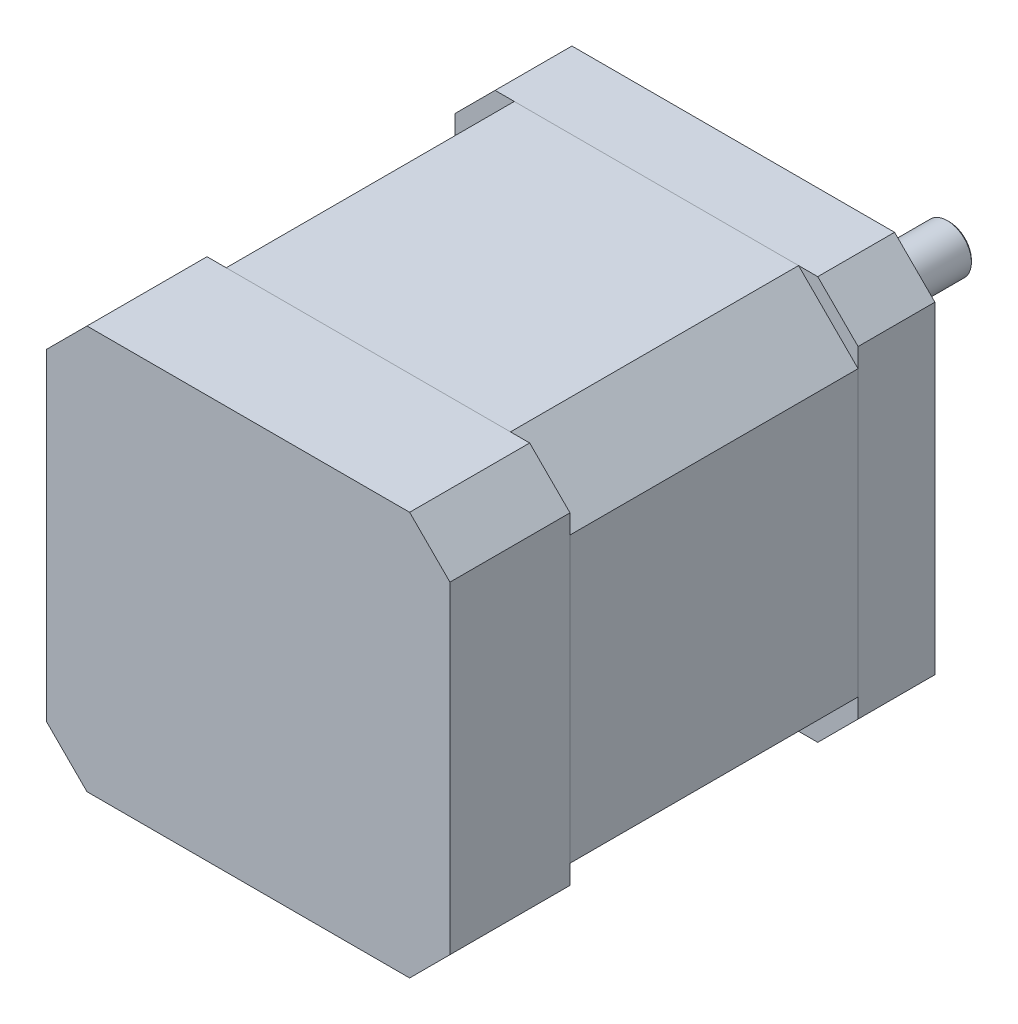
SolidWorks part; units mm, degrees
ref_plane "Plan de face" through (0, 0, 0) normal (0, 0, 1) x (1, 0, 0)
ref_plane "Plan de dessus" through (0, 0, 0) normal (0, 1, 0) x (1, 0, 0)
ref_plane "Plan de droite" through (0, 0, 0) normal (1, 0, 0) x (0, 0, -1)
sketch "Esquisse1" plane through (0, 0, 0) normal (0, 0, 1) x (1, 0, 0)
  line L1 (-21, 21) -> (21, 21)
  line L2 (-21, 21) -> (-21, -21)
  line L3 (-21, -21) -> (21, -21)
  line L4 (21, 21) -> (21, -21)
  line L5 (-21, 21) -> (21, -21) construction
  line L6 (-21, -21) -> (21, 21) construction
  point P0 (0, 0)
  dimension "D1" = 42
  dimension "D2" = 42
extrude "Boss.-Extru.1" add sketch "Esquisse1" along normal blind 8
chamfer "Chanfrein1" distance 4.2 angle 45 4 edges at (-21, -21, 4) (-21, 21, 4) (21, 21, 4) (21, -21, 4)
sketch "Esquisse3" plane through (0, 0, 8) normal (0, 0, 1) x (1, 0, 0)
  line L0 (-21, 14.8) -> (-14.8, 21)
  line L1 (-14.8, 21) -> (14.8, 21)
  line L2 (-21, 14.8) -> (-21, -14.8)
  line L3 (-14.8, -21) -> (14.8, -21)
  line L4 (21, 14.8) -> (21, -14.8)
  line L5 (-21, 21) -> (21, -21) construction
  line L6 (-21, -21) -> (21, 21) construction
  line L7 (14.8, 21) -> (21, 14.8)
  line L8 (14.8, -21) -> (21, -14.8)
  line L9 (-21, -14.8) -> (-14.8, -21)
  point P0 (0, 0)
  dimension "D1" = 42
  dimension "D2" = 42
extrude "Boss.-Extru.2" add sketch "Esquisse3" along normal blind 30 separate body
sketch "Esquisse4" plane through (0, 0, 38) normal (0, 0, 1) x (1, 0, 0)
  line L1 (-21, -21) -> (21, -21)
  line L2 (-21, -21) -> (-21, 21)
  line L3 (-21, 21) -> (21, 21)
  line L4 (21, -21) -> (21, 21)
  line L5 (-21, -21) -> (21, 21) construction
  line L6 (-21, 21) -> (21, -21) construction
  point P0 (0, 0)
  dimension "D1" = 42
  dimension "D2" = 42
extrude "Boss.-Extru.3" add sketch "Esquisse4" along normal blind 12.5 separate body
chamfer "Chanfrein3" distance 4.2 angle 45 4 edges at (21, 21, 44.25) (21, -21, 44.25) (-21, -21, 44.25) (-21, 21, 44.25)
sketch "Esquisse5" plane through (0, 0, 0) normal (0, 0, -1) x (-1, 0, 0)
  circle A0 centre (0, 0) radius 11
  dimension "D1" = 22
extrude "Boss.-Extru.4" add sketch "Esquisse5" along normal blind 2
sketch "Esquisse6" plane through (0, 0, -2) normal (0, 0, -1) x (-1, 0, 0)
  circle A0 centre (0, 0) radius 4.5
  dimension "D1" = 9
extrude "Enlèv. mat.-Extru.1" cut sketch "Esquisse6" against normal blind 3
sketch "Esquisse7" plane through (0, 0, 1) normal (0, 0, -1) x (-1, 0, 0)
  circle A0 centre (0, 0) radius 2.5
  dimension "D1" = 5
extrude "Boss.-Extru.5" add sketch "Esquisse7" along normal blind 23.5
chamfer "Chanfrein4" distance 0.2 angle 45 1 edges at (-2.5, 0, -22.5)
sketch "Esquisse8" plane through (0, 0, 0) normal (0, 0, -1) x (-1, 0, 0)
  line L1 (-15.5, 15.5) -> (15.5, 15.5) construction
  line L2 (-15.5, 15.5) -> (-15.5, -15.5) construction
  line L3 (-15.5, -15.5) -> (15.5, -15.5) construction
  line L4 (15.5, 15.5) -> (15.5, -15.5) construction
  line L5 (-15.5, 15.5) -> (15.5, -15.5) construction
  line L6 (-15.5, -15.5) -> (15.5, 15.5) construction
  circle A0 centre (-15.5, 15.5) radius 1.5
  circle A1 centre (15.5, 15.5) radius 1.5
  circle A2 centre (15.5, -15.5) radius 1.5
  circle A3 centre (-15.5, -15.5) radius 1.5
  point P0 (0, 0)
  dimension "D3" = 3
  dimension "D1" = 31
  dimension "D2" = 31
extrude "Enlèv. mat.-Extru.2" cut sketch "Esquisse8" against normal blind 5
chamfer "Chanfrein5" distance 0.2 angle 45 4 edges at (14, -15.5, 0) (-17, -15.5, 0) (-17, 15.5, 0) (14, 15.5, 0)
sketch "Esquisse9" plane through (-21, 0, 0) normal (-1, 0, 0) x (0, 0, 1)
  line L0 (41.5, 0) -> (38, 0) construction
  line L1 (38, -4) -> (45, -4)
  line L2 (38, -4) -> (38, 4)
  line L3 (38, 4) -> (45, 4)
  line L4 (45, -4) -> (45, 4)
  line L5 (38, -4) -> (45, 4) construction
  line L6 (38, 4) -> (45, -4) construction
  line L7 (38, 16.8) -> (38, -16.8) construction
  point P0 (41.5, 0)
  dimension "D1" = 7
  dimension "D2" = 8
extrude "Enlèv. mat.-Extru.3" cut sketch "Esquisse9" against normal blind 2
